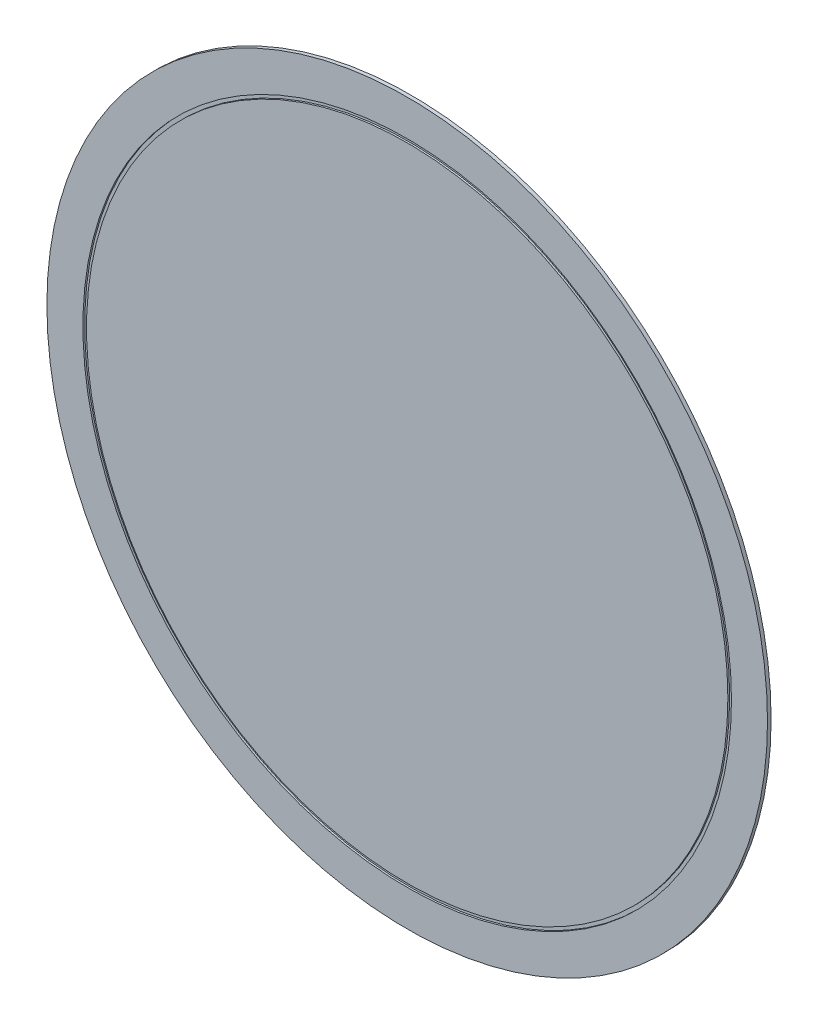
SolidWorks part; units mm, degrees
ref_plane "Front Plane" through (0, 0, 0) normal (0, 0, 1) x (1, 0, 0)
ref_plane "Top Plane" through (0, 0, 0) normal (0, 1, 0) x (1, 0, 0)
ref_plane "Right Plane" through (0, 0, 0) normal (1, 0, 0) x (0, 0, -1)
sketch "Sketch1" plane through (0, 0, 0) normal (0, 0, 1) x (1, 0, 0)
  circle A0 centre (0, 0) radius 254
  dimension "D1" = 508
extrude "Boss-Extrude1" add sketch "Sketch1" along normal blind 2.54
sketch "Sketch2" plane through (0, 0, 2.54) normal (0, 0, 1) x (1, 0, 0)
  circle A0 centre (0, 0) radius 228.6
  circle A1 centre (0, 0) radius 226.06
  dimension "D1" = 457.2
  dimension "D2" = 452.12
extrude "Cut-Extrude1" cut sketch "Sketch2" against normal blind 1.27
